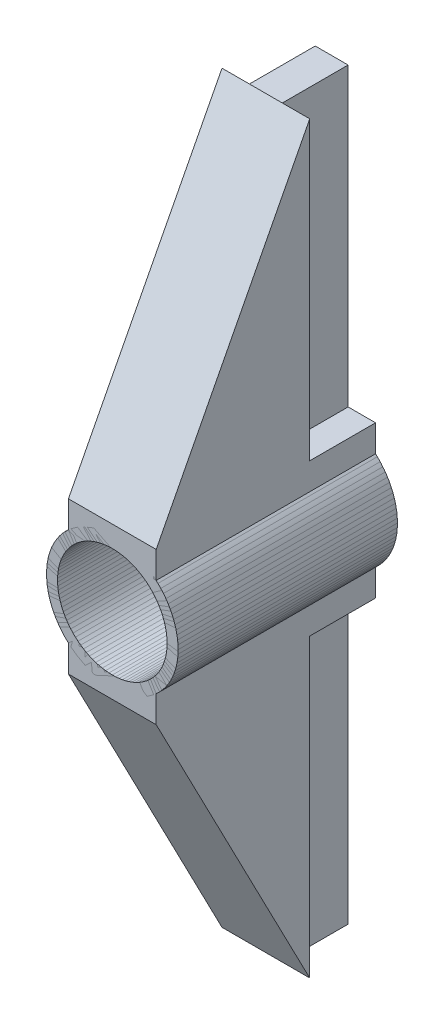
SolidWorks part; units mm, degrees
ref_plane "Front Plane" through (0, 0, 0) normal (0, 0, 1) x (1, 0, 0)
ref_plane "Top Plane" through (0, 0, 0) normal (0, 1, 0) x (1, 0, 0)
ref_plane "Right Plane" through (0, 0, 0) normal (1, 0, 0) x (0, 0, -1)
other "Configuration Table"
sketch "Sketch1" plane through (0, 0, 0) normal (0, 0, 1) x (1, 0, 0)
  circle A0 centre (0, 0) radius 5
  circle A1 centre (0, 0) radius 6
  dimension "D1" = 10
  dimension "D2" = 12
extrude "Boss-Extrude1" add sketch "Sketch1" along normal blind 20
sketch "Sketch2" plane through (0, 0, 0) normal (1, 0, 0) x (0, 0, -1)
  line L0 (-20, 6.9198) -> (-20, 3.9198)
  line L2 (-20, 3.9198) -> (0, 3.9198)
  line L3 (-20, 6) -> (-20, -6) construction
  line L5 (0, 3.9198) -> (0, 33.9198)
  line L6 (-20, 6.9198) -> (-6, 33.9198)
  line L7 (-6, 33.9198) -> (0, 33.9198)
  dimension "D1" = 30
  dimension "D2" = 6
  dimension "D3" = 3
extrude "Boss-Extrude2" add sketch "Sketch2" along normal mid plane 8
sketch "Sketch3" plane through (0, 33.9198, 0) normal (0, 1, 0) x (1, 0, 0)
  line L0 (-4, 0) -> (-1.5, 0)
  line L1 (4, 0) -> (-4, 0) construction
  line L2 (-1.5, 0) -> (-1.5, -6)
  line L3 (4, -6) -> (-4, -6) construction
  line L4 (-1.5, -6) -> (-4, -6)
  line L5 (-4, -6) -> (-4, 0)
  line L6 (4, 0) -> (1.5, 0)
  line L7 (1.5, 0) -> (1.5, -6)
  line L8 (1.5, -6) -> (4, -6)
  line L9 (4, -6) -> (4, 0)
  dimension "D1" = 2.5
extrude "Cut-Extrude1" cut sketch "Sketch3" against normal up to vertex (27 mm away) up to point (4, 6.9198, 20)
move or copy body "Body-Move/Copy1" bodies to move or copy 104 copy yes number of copies 1 rotation origin (0, 0, 0) rotation axis (0, 0, 1) rotation angle 180
sketch "Sketch4" plane through (0, 0, 0) normal (0, 0, -1) x (-1, 0, 0)
  circle A0 centre (0, 0) radius 5
extrude "Cut-Extrude2" cut sketch "Sketch4" against normal through all
